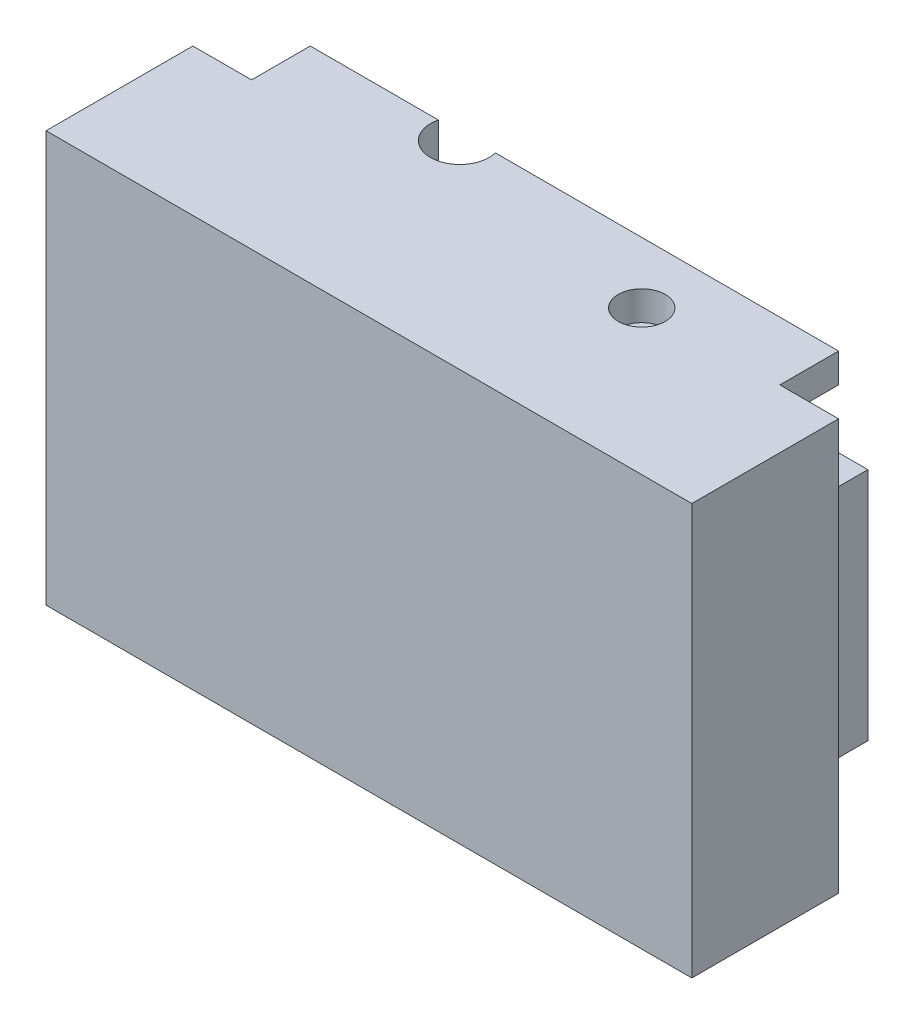
SolidWorks part; units mm, degrees
ref_plane "Front Plane" through (0, 0, 0) normal (0, 0, 1) x (1, 0, 0)
ref_plane "Top Plane" through (0, 0, 0) normal (0, 1, 0) x (1, 0, 0)
ref_plane "Right Plane" through (0, 0, 0) normal (1, 0, 0) x (0, 0, -1)
sketch "Sketch1" plane through (0, 0, 0) normal (0, 0, 1) x (1, 0, 0)
  line L1 (0, 0) -> (110, 0)
  line L2 (0, 0) -> (0, 70)
  line L3 (0, 70) -> (110, 70)
  line L4 (110, 0) -> (110, 70)
  dimension "D1" = 110
  dimension "D2" = 70
extrude "Boss-Extrude1" add sketch "Sketch1" along normal blind 5
sketch "Sketch2" plane through (0, 0, 0) normal (0, 0, -1) x (-1, 0, 0)
  line L0 (0, 0) -> (-110, 0) construction
  line L1 (-110, 70) -> (-100, 70)
  line L2 (-110, 70) -> (-110, 0)
  line L3 (-110, 0) -> (-100, 0)
  line L4 (-100, 70) -> (-100, 0)
  line L6 (0, 70) -> (-10, 70)
  line L7 (0, 70) -> (0, 0)
  line L8 (0, 0) -> (-10, 0)
  line L9 (-10, 70) -> (-10, 0)
  line L10 (-100, 70) -> (-10, 70)
  line L11 (-100, 70) -> (-100, 60)
  line L12 (-100, 60) -> (-10, 60)
  line L13 (-10, 70) -> (-10, 60)
  line L14 (-10, 10) -> (-100, 10)
  line L15 (-10, 10) -> (-10, 0)
  line L16 (-10, 0) -> (-100, 0)
  line L17 (-100, 10) -> (-100, 0)
  line M3 (0, 0) -> (0, 70)
  line M4 (0, 70) -> (-110, 70)
  line M5 (-110, 70) -> (-110, 0)
  line M6 (-110, 0) -> (0, 0)
  dimension "D1" = 10
  dimension "D2" = 10
  dimension "D3" = 10
  dimension "D4" = 10
extrude "Boss-Extrude2" add sketch "Sketch2" along normal blind 20 contours L4 L12 L9 M4 | L4 M4 M5 M6 | L9 M4 M6 M3 | L9 L14 L4 M6
sketch "Sketch6" plane through (0, 0, -20) normal (0, 0, -1) x (-1, 0, 0)
  line L0 (-10, 60) -> (-100, 60)
  line L1 (-10, 60) -> (-10, 70.1355)
  line L2 (-100, 60) -> (-100, 70.1355)
  line L3 (-10, 70.1355) -> (-100, 70.1355)
  line L5 (-10, 60) -> (-30, 60)
  line L6 (-10, 60) -> (-10, 65)
  line L7 (-10, 65) -> (-30, 65)
  line L8 (-30, 60) -> (-30, 65)
  line L9 (-45, 60) -> (-65, 60)
  line L10 (-45, 60) -> (-45, 65)
  line L11 (-45, 65) -> (-65, 65)
  line L12 (-65, 60) -> (-65, 65)
  line L13 (-100, 60) -> (-85, 60)
  line L14 (-100, 60) -> (-100, 65)
  line L15 (-100, 65) -> (-85, 65)
  line L16 (-85, 60) -> (-85, 65)
  line M11 (0, 70) -> (-110, 70)
  line M27 (-100, 60) -> (-10, 60)
  dimension "D1" = 5
  dimension "D2" = 5
  dimension "D3" = 5
  dimension "D4" = 15
  dimension "D5" = 20
  dimension "D6" = 20
  dimension "D7" = 15
extrude "Boss-Extrude5" add sketch "Sketch6" along normal blind 10 contours L16 L0 L12 L11 L10 L8 L7 L1 L2 L15 M27 M11
sketch "Sketch7" plane through (0, 70, 0) normal (0, 1, 0) x (1, 0, 0)
  line L0 (0, -5) -> (0, 20) construction
  line L1 (10, 30) -> (100, 30) construction
  circle A0 centre (36.69, 28.79) radius 5
  dimension "D3" = 10
  dimension "D1" = 36.69
  dimension "D2" = 1.21
extrude "Cut-Extrude2" cut sketch "Sketch7" against normal blind 10 contours A0
sketch "Sketch8" plane through (0, 70, 0) normal (0, 1, 0) x (1, 0, 0)
  line L0 (110, -5) -> (110, 20) construction
  line L1 (41.5414, 30) -> (100, 30) construction
  circle A0 centre (76.88, 19.59) radius 4
  dimension "D1" = 8
  dimension "D2" = 33.12
  dimension "D3" = 10.41
extrude "Cut-Extrude3" cut sketch "Sketch8" against normal blind 5
sketch "Sketch9" plane through (0, 0, -20) normal (0, 0, -1) x (-1, 0, 0)
  line L1 (-100, 55) -> (-105, 55)
  line L2 (-100, 55) -> (-100, 15)
  line L3 (-100, 15) -> (-105, 15)
  line L4 (-105, 55) -> (-105, 15)
  line L5 (-10, 55) -> (-5, 55)
  line L6 (-10, 55) -> (-10, 15)
  line L7 (-10, 15) -> (-5, 15)
  line L8 (-5, 55) -> (-5, 15)
  line L9 (-100, 60) -> (-100, 10) construction
  line L10 (-10, 60) -> (-10, 10) construction
  point P8 (-100, 35)
  point P11 (-100, 35)
  point P12 (-10, 35)
  point P15 (-10, 35)
  dimension "D1" = 5
  dimension "D2" = 5
  dimension "D3" = 40
  dimension "D4" = 40
extrude "Boss-Extrude6" add sketch "Sketch9" along normal blind 10
sketch "Sketch10" plane through (0, 0, -20) normal (0, 0, -1) x (-1, 0, 0)
  line L0 (-100, 10) -> (-10, 10)
  line L1 (-100, 10) -> (-100, -0.0752)
  line L2 (-10, 10) -> (-10, -0.0752)
  line L3 (-100, -0.0752) -> (-10, -0.0752)
extrude "Boss-Extrude7" add sketch "Sketch10" along normal blind 10
sketch "Sketch11" plane through (0, 10, 0) normal (0, 1, 0) x (1, 0, 0)
  line L0 (10, 30) -> (100, 30) construction
  line L1 (35, 30) -> (75, 30)
  line L2 (35, 30) -> (35, 20)
  line L3 (35, 20) -> (75, 20)
  line L4 (75, 30) -> (75, 20)
  point P4 (55, 30)
  point P7 (55, 30)
  dimension "D1" = 40
  dimension "D2" = 10
extrude "Cut-Extrude4" cut sketch "Sketch11" against normal blind 5
